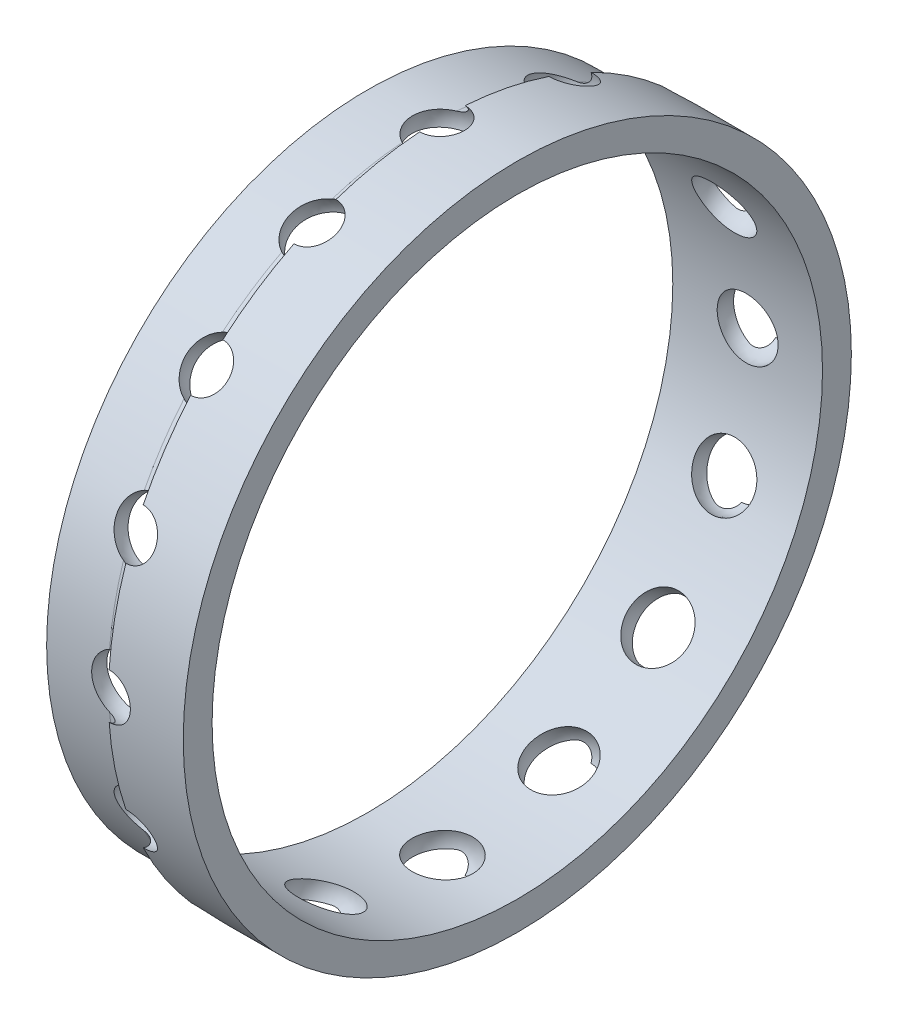
SolidWorks part; units mm, degrees
ref_plane "Front Plane" through (0, 0, 0) normal (0, 0, 1) x (1, 0, 0)
ref_plane "Top Plane" through (0, 0, 0) normal (0, 1, 0) x (1, 0, 0)
ref_plane "Right Plane" through (0, 0, 0) normal (1, 0, 0) x (0, 0, -1)
ref_plane "Plane1" through (0, 0, 0) normal (0, 0, 1) x (1, 0, 0)
sketch "Sketch1" plane through (0, 0, 0) normal (0, 0, 1) x (1, 0, 0)
  line L0 (0, 29.355) -> (14.4, 29.355)
  line L1 (14.4, 29.355) -> (14.4, 32.13)
  line L2 (14.4, 32.13) -> (7.2, 32.13)
  line L3 (5.94, 30.87) -> (0, 30.87)
  line L4 (0, 30.87) -> (0, 29.355)
  line L5 (14.4, 0) -> (0, 0) construction
  arc A0 (7.2, 32.13) -> (5.94, 30.87) centre (5.94, 32.13) cw
revolve "Revolve1" add sketch "Sketch1" angle 360 about L5
ref_plane "Plane2" through (0, 0, 0) normal (0, 0, 1) x (1, 0, 0)
sketch "Sketch2" plane through (0, 0, 0) normal (0, 0, 1) x (1, 0, 0)
  line L0 (10.2, 30) -> (4.2, 30)
  line L1 (10.2, 30) -> (4.2, 30) construction
  arc A0 (4.2, 30) -> (10.2, 30) centre (7.2, 30) cw
revolve "Cut-Revolve1" cut sketch "Sketch2" angle 360 about L1
ref_plane "Plane3" through (0, 0, 11.4805) normal (0, 0, 1) x (1, 0, 0)
sketch "Sketch3" plane through (0, 0, 11.4805) normal (0, 0, 1) x (1, 0, 0)
  line L0 (10.2, 27.7164) -> (4.2, 27.7164)
  line L1 (10.2, 27.7164) -> (4.2, 27.7164) construction
  arc A0 (4.2, 27.7164) -> (10.2, 27.7164) centre (7.2, 27.7164) cw
revolve "Cut-Revolve2" cut sketch "Sketch3" angle 360 about L1
ref_plane "Plane4" through (0, 0, 21.2132) normal (0, 0, 1) x (1, 0, 0)
sketch "Sketch4" plane through (0, 0, 21.2132) normal (0, 0, 1) x (1, 0, 0)
  line L0 (10.2, 21.2132) -> (4.2, 21.2132)
  line L1 (10.2, 21.2132) -> (4.2, 21.2132) construction
  arc A0 (4.2, 21.2132) -> (10.2, 21.2132) centre (7.2, 21.2132) cw
revolve "Cut-Revolve3" cut sketch "Sketch4" angle 360 about L1
ref_plane "Plane5" through (0, 0, 27.7164) normal (0, 0, 1) x (1, 0, 0)
sketch "Sketch5" plane through (0, 0, 27.7164) normal (0, 0, 1) x (1, 0, 0)
  line L0 (10.2, 11.4805) -> (4.2, 11.4805)
  line L1 (10.2, 11.4805) -> (4.2, 11.4805) construction
  arc A0 (4.2, 11.4805) -> (10.2, 11.4805) centre (7.2, 11.4805) cw
revolve "Cut-Revolve4" cut sketch "Sketch5" angle 360 about L1
ref_plane "Plane6" through (0, 0, 30) normal (0, 0, 1) x (1, 0, 0)
sketch "Sketch6" plane through (0, 0, 30) normal (0, 0, 1) x (1, 0, 0)
  line L0 (10.2, 0) -> (4.2, 0)
  line L1 (10.2, 0) -> (4.2, 0) construction
  arc A0 (4.2, 0) -> (10.2, 0) centre (7.2, 0) cw
revolve "Cut-Revolve5" cut sketch "Sketch6" angle 360 about L1
ref_plane "Plane7" through (0, 0, 27.7164) normal (0, 0, 1) x (1, 0, 0)
sketch "Sketch7" plane through (0, 0, 27.7164) normal (0, 0, 1) x (1, 0, 0)
  line L0 (10.2, -11.4805) -> (4.2, -11.4805)
  line L1 (10.2, -11.4805) -> (4.2, -11.4805) construction
  arc A0 (4.2, -11.4805) -> (10.2, -11.4805) centre (7.2, -11.4805) cw
revolve "Cut-Revolve6" cut sketch "Sketch7" angle 360 about L1
ref_plane "Plane8" through (0, 0, 21.2132) normal (0, 0, 1) x (1, 0, 0)
sketch "Sketch8" plane through (0, 0, 21.2132) normal (0, 0, 1) x (1, 0, 0)
  line L0 (10.2, -21.2132) -> (4.2, -21.2132)
  line L1 (10.2, -21.2132) -> (4.2, -21.2132) construction
  arc A0 (4.2, -21.2132) -> (10.2, -21.2132) centre (7.2, -21.2132) cw
revolve "Cut-Revolve7" cut sketch "Sketch8" angle 360 about L1
ref_plane "Plane9" through (0, 0, 11.4805) normal (0, 0, 1) x (1, 0, 0)
sketch "Sketch9" plane through (0, 0, 11.4805) normal (0, 0, 1) x (1, 0, 0)
  line L0 (10.2, -27.7164) -> (4.2, -27.7164)
  line L1 (10.2, -27.7164) -> (4.2, -27.7164) construction
  arc A0 (4.2, -27.7164) -> (10.2, -27.7164) centre (7.2, -27.7164) cw
revolve "Cut-Revolve8" cut sketch "Sketch9" angle 360 about L1
ref_plane "Plane10" through (0, 0, 0) normal (0, 0, 1) x (1, 0, 0)
sketch "Sketch10" plane through (0, 0, 0) normal (0, 0, 1) x (1, 0, 0)
  line L0 (10.2, -30) -> (4.2, -30)
  line L1 (10.2, -30) -> (4.2, -30) construction
  arc A0 (4.2, -30) -> (10.2, -30) centre (7.2, -30) cw
revolve "Cut-Revolve9" cut sketch "Sketch10" angle 360 about L1
ref_plane "Plane11" through (0, 0, -11.4805) normal (0, 0, 1) x (1, 0, 0)
sketch "Sketch11" plane through (0, 0, -11.4805) normal (0, 0, 1) x (1, 0, 0)
  line L0 (10.2, -27.7164) -> (4.2, -27.7164)
  line L1 (10.2, -27.7164) -> (4.2, -27.7164) construction
  arc A0 (4.2, -27.7164) -> (10.2, -27.7164) centre (7.2, -27.7164) cw
revolve "Cut-Revolve10" cut sketch "Sketch11" angle 360 about L1
ref_plane "Plane12" through (0, 0, -21.2132) normal (0, 0, 1) x (1, 0, 0)
sketch "Sketch12" plane through (0, 0, -21.2132) normal (0, 0, 1) x (1, 0, 0)
  line L0 (10.2, -21.2132) -> (4.2, -21.2132)
  line L1 (10.2, -21.2132) -> (4.2, -21.2132) construction
  arc A0 (4.2, -21.2132) -> (10.2, -21.2132) centre (7.2, -21.2132) cw
revolve "Cut-Revolve11" cut sketch "Sketch12" angle 360 about L1
ref_plane "Plane13" through (0, 0, -27.7164) normal (0, 0, 1) x (1, 0, 0)
sketch "Sketch13" plane through (0, 0, -27.7164) normal (0, 0, 1) x (1, 0, 0)
  line L0 (10.2, -11.4805) -> (4.2, -11.4805)
  line L1 (10.2, -11.4805) -> (4.2, -11.4805) construction
  arc A0 (4.2, -11.4805) -> (10.2, -11.4805) centre (7.2, -11.4805) cw
revolve "Cut-Revolve12" cut sketch "Sketch13" angle 360 about L1
ref_plane "Plane14" through (0, 0, -30) normal (0, 0, 1) x (1, 0, 0)
sketch "Sketch14" plane through (0, 0, -30) normal (0, 0, 1) x (1, 0, 0)
  line L0 (10.2, 0) -> (4.2, 0)
  line L1 (10.2, 0) -> (4.2, 0) construction
  arc A0 (4.2, 0) -> (10.2, 0) centre (7.2, 0) cw
revolve "Cut-Revolve13" cut sketch "Sketch14" angle 360 about L1
ref_plane "Plane15" through (0, 0, -27.7164) normal (0, 0, 1) x (1, 0, 0)
sketch "Sketch15" plane through (0, 0, -27.7164) normal (0, 0, 1) x (1, 0, 0)
  line L0 (10.2, 11.4805) -> (4.2, 11.4805)
  line L1 (10.2, 11.4805) -> (4.2, 11.4805) construction
  arc A0 (4.2, 11.4805) -> (10.2, 11.4805) centre (7.2, 11.4805) cw
revolve "Cut-Revolve14" cut sketch "Sketch15" angle 360 about L1
ref_plane "Plane16" through (0, 0, -21.2132) normal (0, 0, 1) x (1, 0, 0)
sketch "Sketch16" plane through (0, 0, -21.2132) normal (0, 0, 1) x (1, 0, 0)
  line L0 (10.2, 21.2132) -> (4.2, 21.2132)
  line L1 (10.2, 21.2132) -> (4.2, 21.2132) construction
  arc A0 (4.2, 21.2132) -> (10.2, 21.2132) centre (7.2, 21.2132) cw
revolve "Cut-Revolve15" cut sketch "Sketch16" angle 360 about L1
ref_plane "Plane17" through (0, 0, -11.4805) normal (0, 0, 1) x (1, 0, 0)
sketch "Sketch17" plane through (0, 0, -11.4805) normal (0, 0, 1) x (1, 0, 0)
  line L0 (10.2, 27.7164) -> (4.2, 27.7164)
  line L1 (10.2, 27.7164) -> (4.2, 27.7164) construction
  arc A0 (4.2, 27.7164) -> (10.2, 27.7164) centre (7.2, 27.7164) cw
revolve "Cut-Revolve16" cut sketch "Sketch17" angle 360 about L1
